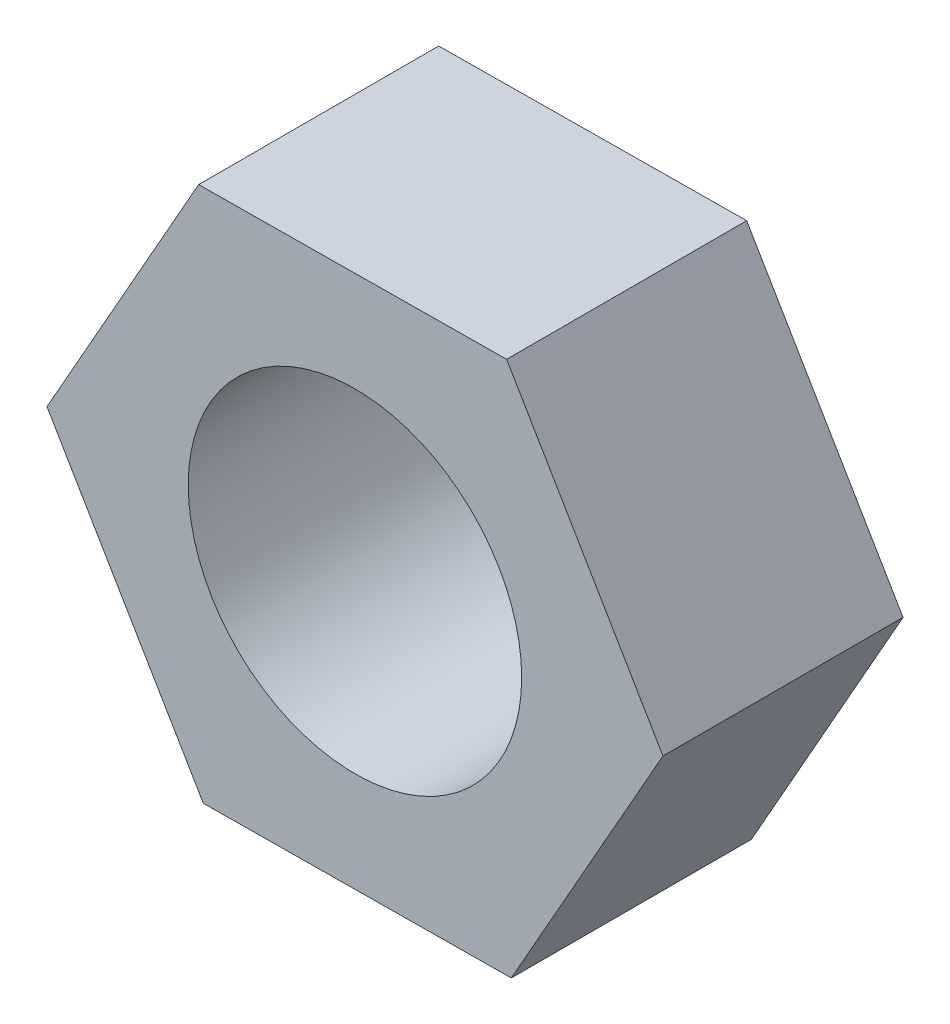
SolidWorks part; units mm, degrees
ref_plane "前视基准面" through (0, 0, 0) normal (0, 0, 1) x (1, 0, 0)
ref_plane "上视基准面" through (0, 0, 0) normal (0, 1, 0) x (1, 0, 0)
ref_plane "右视基准面" through (0, 0, 0) normal (1, 0, 0) x (0, 0, -1)
sketch "草图1" plane through (0, 0, 0) normal (0, 0, 1) x (1, 0, 0)
  line L1 (2.3445, -3.9795) -> (4.6186, 0.0407)
  line L2 (4.6186, 0.0407) -> (2.2741, 4.0202)
  line L3 (2.2741, 4.0202) -> (-2.3445, 3.9795)
  line L4 (-2.3445, 3.9795) -> (-4.6186, -0.0407)
  line L5 (-4.6186, -0.0407) -> (-2.2741, -4.0202)
  line L6 (-2.2741, -4.0202) -> (2.3445, -3.9795)
  circle A0 centre (0, 0) radius 4 construction
  circle A1 centre (0, 0) radius 2.5
  dimension "D1" = 5
  dimension "D2" = 8
extrude "凸台-拉伸1" add sketch "草图1" along normal blind 3.6
